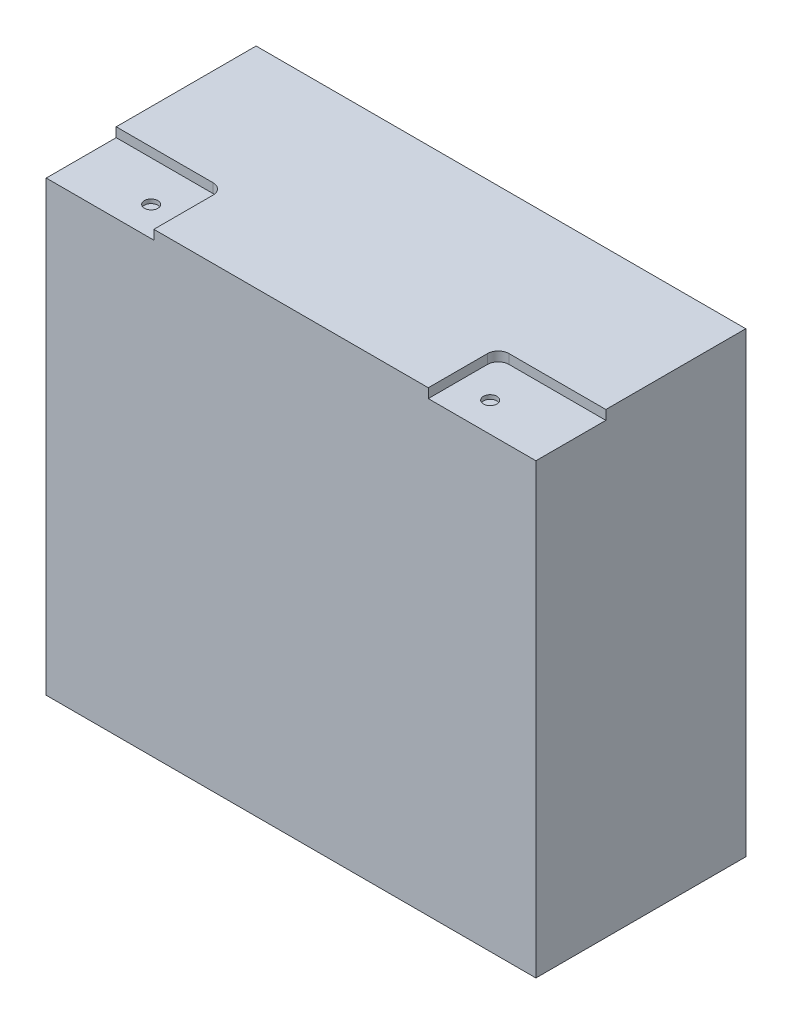
SolidWorks part; units mm, degrees
ref_plane "Front Plane" through (0, 0, 0) normal (0, 0, 1) x (1, 0, 0)
ref_plane "Top Plane" through (0, 0, 0) normal (0, 1, 0) x (1, 0, 0)
ref_plane "Right Plane" through (0, 0, 0) normal (1, 0, 0) x (0, 0, -1)
sketch "Sketch1" plane through (0, 0, 0) normal (0, 1, 0) x (1, 0, 0)
  line L1 (-91, -39) -> (91, -39)
  line L2 (-91, -39) -> (-91, 39)
  line L3 (-91, 39) -> (91, 39)
  line L4 (91, -39) -> (91, 39)
  line L5 (-91, -39) -> (91, 39) construction
  line L6 (-91, 39) -> (91, -39) construction
  point P0 (0, 0)
  dimension "D1" = 182
  dimension "D2" = 78
extrude "Boss-Extrude1" add sketch "Sketch1" along normal blind 170
sketch "Sketch3" plane through (0, 170, 0) normal (0, 1, 0) x (1, 0, 0)
  line L0 (63, -28) -> (91, -28) construction
  line L1 (91, -39) -> (91, 39) construction
  line L2 (-91, -39) -> (91, -39) construction
  line L3 (0, -1000) -> (0, 49000) construction
  circle A0 centre (63, -28) radius 2.5
  circle A1 centre (-63, -28) radius 2.5
  dimension "D3" = 5
  dimension "D1" = 28
  dimension "D2" = 11
extrude "Cut-Extrude1" cut sketch "Sketch3" against normal blind 5
sketch "Sketch4" plane through (0, 170, 0) normal (0, 1, 0) x (1, 0, 0)
  line L1 (-91, -39) -> (-51, -39)
  line L2 (-91, -39) -> (-91, -13)
  line L3 (-91, -13) -> (-51, -13)
  line L4 (-51, -39) -> (-51, -13)
  line L5 (91, -39) -> (51, -39)
  line L6 (91, -39) -> (91, -13)
  line L7 (91, -13) -> (51, -13)
  line L8 (51, -39) -> (51, -13)
  dimension "D1" = 40
  dimension "D2" = 26
extrude "Cut-Extrude2" cut sketch "Sketch4" against normal blind 3.5
fillet "Fillet1" radius 4 2 edges at (51, 168.25, 13) (-51, 168.25, 13)
